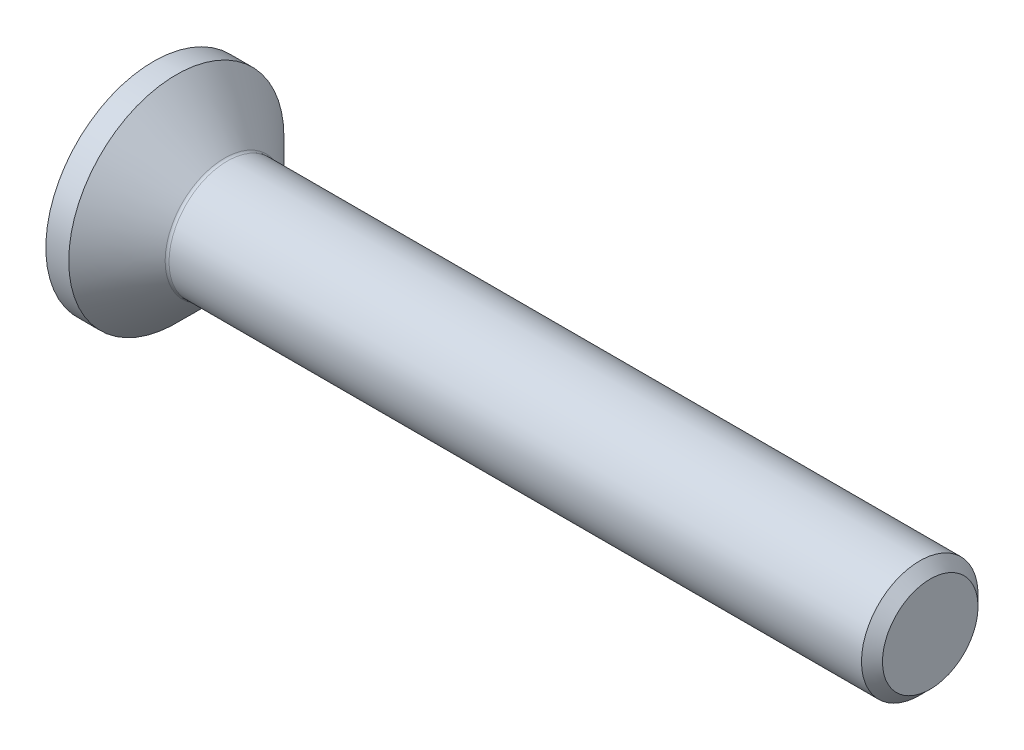
SolidWorks part; units mm, degrees
ref_plane "Front" through (0, 0, 0) normal (0, 0, 1) x (1, 0, 0)
ref_plane "Top" through (0, 0, 0) normal (0, 1, 0) x (1, 0, 0)
ref_plane "Right" through (0, 0, 0) normal (1, 0, 0) x (0, 0, -1)
sketch "Sketch1" plane through (0, 0, 0) normal (0, 0, 1) x (1, 0, 0)
  line L0 (0, 0) -> (0, 3.36)
  line L1 (0, 3.36) -> (1.86, 1.5)
  line L2 (1.86, 1.5) -> (20, 1.5)
  line L3 (20, 1.5) -> (20, 0)
  line L4 (20, 0) -> (0, 0)
  line L5 (-0.5871, 0) -> (5.4927, 0) construction
  dimension "l" = 20
  dimension "k" = 1.86
  dimension "d" = 3
  dimension "D1" = 45
revolve "Base" add sketch "Sketch1" angle 360 about L5
cosmetic thread "ThreadCosmetic1" parameters "b"=18, "D2"=2.459
sketch "Sketch2" plane through (0, 0, 0) normal (1, 0, 0) x (0, 0, -1)
  line L1 (1.1547, 0) -> (0.5774, 1)
  line L2 (0.5774, 1) -> (-0.5774, 1)
  line L3 (-0.5774, 1) -> (-1.1547, 0)
  line L4 (-1.1547, 0) -> (-0.5774, -1)
  line L5 (-0.5774, -1) -> (0.5774, -1)
  line L6 (0.5774, -1) -> (1.1547, 0)
  circle A0 centre (0, 0) radius 1 construction
  dimension "s" = 2
extrude "HexagonSocket" cut sketch "Sketch2" along normal blind 1.1
sketch "Sketch3" plane through (0, 0, 0) normal (0, 0, 1) x (1, 0, 0)
  line L0 (-0.4391, 0) -> (4.425, 0) construction
  line L1 (1.1, 0) -> (1.1, -1) construction
  line L2 (1.1, 1) -> (1.6774, 0)
  line L3 (1.6774, 0) -> (1.1, -1) construction
  line L4 (1.1, 1) -> (1.1, 0)
  line L5 (1.1, 0) -> (1.6774, 0)
  line L7 (1.1, 1) -> (1.1, 0) construction
  dimension "D1" = 120
revolve "Cut-Revolve1" cut sketch "Sketch3" angle 360 about L0
fillet "HeadFillet" radius 0.1 1 edges at (1.86, 0, 1.5)
chamfer "Chamfer" distance 0.2705 angle 45 1 edges at (20, 0, 1.5)
sketch "Sketch4" plane through (0, 0, 0) normal (0, 1, 0) x (1, 0, 0)
  line L0 (11.8531, 0) -> (-2.694, 0) construction
  line L1 (-2, 7.77) -> (3, 7.77)
  line L2 (-2, 7.77) -> (-2, 2.77)
  line L3 (-2, 2.77) -> (3, 2.77)
  line L4 (3, 7.77) -> (3, 2.77)
  line L5 (0, 3.36) -> (0, -3.36) construction
  dimension "dk" = 5.54
  dimension "D2" = 2
  dimension "D3" = 5
  dimension "D4" = 5
revolve "Cut-Revolve2" cut sketch "Sketch4" angle 360 about L0
sketch "Sketch5" plane through (0, 0, 0) normal (0, 0, 1) x (1, 0, 0)
  line L0 (19.7295, 1.2657) -> (19.8647, 1.5)
  line L1 (19.8647, 1.5) -> (19.8647, 1.7705)
  line L2 (19.8647, 1.7705) -> (19.5942, 1.7705)
  line L3 (19.5942, 1.7705) -> (19.5942, 1.5)
  line L4 (19.5942, 1.5) -> (19.7295, 1.2657)
  line L5 (0, 0) -> (10.6885, 0) construction
  line L6 (19.7295, 1.5) -> (19.7295, -1.5) construction
  dimension "D1" = 3
  dimension "D2" = 0.2705
revolve "Cut-Revolve10" [suppressed] cut sketch "Sketch5" angle 360 about L5
pattern_linear "LPattern10" [suppressed] count 55 spacing 0.3246 along (1, 0, 0)
equation "\"D1@Chamfer\" = (  \"d@Sketch1\" - \"D2@ThreadCosmetic1\" )  / 2"
equation "\"D1@Sketch5\" = \"d@Sketch1\""
equation "\"D2@Sketch5\" =  ( \"d@Sketch1\" - \"D2@ThreadCosmetic1\" )  / 2"
equation "\"D3@LPattern10\" = \"D2@Sketch5\" * 1.2"
equation "\"D1@LPattern10\" = \"b@ThreadCosmetic1\" / \"D3@LPattern10\""
